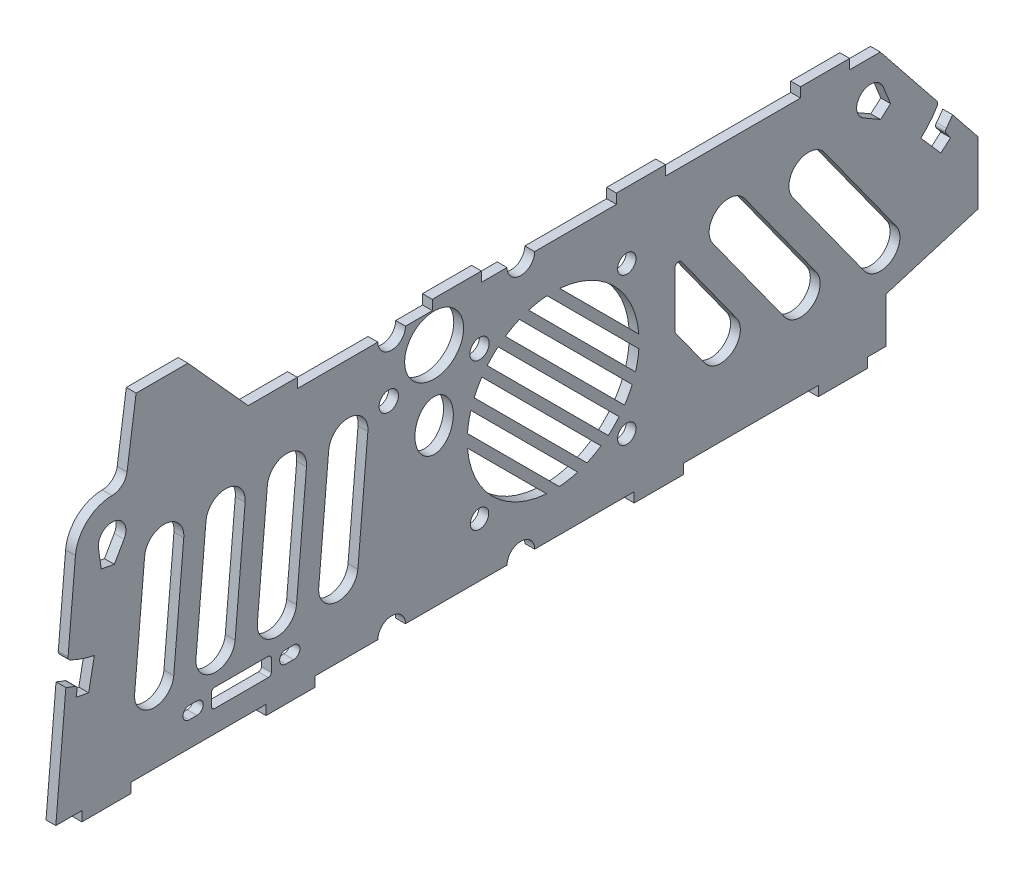
SolidWorks part; units mm, degrees
ref_plane "前视基准面" through (0, 0, 0) normal (0, 0, 1) x (1, 0, 0)
ref_plane "上视基准面" through (0, 0, 0) normal (0, 1, 0) x (1, 0, 0)
ref_plane "右视基准面" through (0, 0, 0) normal (1, 0, 0) x (0, 0, -1)
sketch "右侧结构" plane through (0, 0, 0) normal (1, 0, 0) x (0, 0, -1)
  line L1 (-96.6617, 0) -> (38.5883, 0)
  line L20 (-91.0447, 17.4465) -> (-91.3082, 16.0715)
  line L21 (36.0883, 36) -> (46.5716, 23.9389) construction
  line L22 (37.6933, 42) -> (-87.4892, 42)
  line L23 (-93.4664, 36.5229) -> (-96.6617, 0) construction
  line L25 (38.5883, 0) -> (38.5883, 40.8804) construction
  line L26 (38.5883, 40.8804) -> (37.6933, 42) construction
  line L36 (44.3048, 26.5469) -> (46.5716, 23.9389)
  line L39 (-87.4892, 36) -> (-91.0447, 17.4465) construction
  line L42 (-90.3859, 20.8839) -> (-91.0447, 17.4465)
  line L45 (-93.4664, 36.5229) -> (-94.7017, 22.4034)
  line L48 (-91.3082, 16.0715) -> (-93.3706, 16.4667)
  line L51 (-93.3706, 16.4667) -> (-93.0851, 17.9567)
  line L54 (46.5716, 23.9389) -> (47.5556, 22.8068)
  line L57 (38.5883, 40.8804) -> (53.614, 22.0824) construction
  line L60 (53.614, 22.0824) -> (53.614, 11.8778)
  line L66 (38.5883, 7.3637) -> (38.5883, 0)
  line L69 (47.5556, 22.8068) -> (49.1406, 24.1844)
  line L70 (49.1406, 24.1844) -> (48.1365, 25.5019)
  line L72 (38.1766, 36.8375) -> (39.3635, 33.8782)
  line L73 (39.3635, 33.8782) -> (38.5483, 33.1697)
  line L74 (38.5483, 33.1697) -> (37.7332, 32.4612)
  line L75 (37.7332, 32.4612) -> (34.968, 34.0487)
  line L77 (-88.195, 32.317) -> (-89.2557, 32.5203)
  line L78 (-89.2557, 32.5203) -> (-89.7157, 35.6754)
  line L88 (37.6933, 42) -> (47.164, 30.1517)
  line L91 (-88.195, 32.317) -> (-87.1343, 32.1138)
  line L92 (-87.1343, 32.1138) -> (-85.5405, 34.8753)
  line L97 (42.0237, 24.9708) -> (34.3307, 34.5952) construction
  line L107 (49.4706, 27.266) -> (53.614, 22.0824)
  line L108 (53.614, 11.8778) -> (38.5883, 7.3637)
  line L109 (42.0237, 24.9708) -> (44.209, 22.2369) construction
  line L110 (-95.0276, 18.6781) -> (-96.6617, 0)
  arc A0 (-87.4892, 42) -> (-93.4664, 36.5229) centre (-87.4892, 36) ccw
  circle A21 centre (36.0883, 36) radius 2.25
  arc A23 (47.164, 30.1517) -> (42.0237, 24.9708) centre (36.0883, 36) cw construction
  arc A24 (49.4706, 27.266) -> (44.209, 22.2369) centre (36.0883, 36) cw construction
  arc A25 (47.164, 30.1517) -> (44.3048, 26.5469) centre (36.0883, 36) cw
  arc A28 (49.4706, 27.266) -> (46.5716, 23.9389) centre (36.0883, 36) cw
  circle A31 centre (-87.4892, 36) radius 2.25
  arc A32 (-94.7017, 22.4034) -> (-90.3859, 20.8839) centre (-87.4892, 36) ccw
  arc A33 (-95.0276, 18.6781) -> (-91.0447, 17.4465) centre (-87.4892, 36) ccw
  arc A34 (-44.1822, 42) -> (-39.6822, 42) centre (-41.9322, 42) ccw
  arc A35 (-23.1322, 42) -> (-18.6322, 42) centre (-20.8822, 42) ccw
  arc A37 (-44.1822, 0) -> (-39.6822, 0) centre (-41.9322, 0) cw
  arc A38 (-23.1322, 0) -> (-18.6322, 0) centre (-20.8822, 0) cw
  dimension "D1" = 6
  dimension "D11" = 135.25
  dimension "D13" = 4.5
  dimension "D14" = 6
  dimension "D19" = 3.5
  dimension "D20" = 2.25
  dimension "D30" = 3.75
  dimension "D2" = 42
  dimension "D4" = 7.3637
  dimension "D5" = 15.3911
  dimension "D6" = 21.05
  dimension "D7" = 74.4962
  dimension "D12" = 85
  dimension "D16" = 3.5
  dimension "D17" = 5
  dimension "D18" = 2.5
  dimension "D23" = 1.4
  dimension "D24" = 2.1
  dimension "D25" = 12.3211
  dimension "D26" = 1.5
  dimension "D27" = 2.1
  dimension "D28" = 1.08
  dimension "D29" = 1.08
  dimension "D31" = 1.08
  dimension "D32" = 3.75
  dimension "D33" = 1.08
extrude "凸台-拉伸1" add sketch "右侧结构" along normal blind 1.6
sketch "草图2" plane through (0, 0, 0) normal (1, 0, 0) x (0, 0, -1)
  line L0 (35.5883, 0) -> (35.5883, -1.6)
  line L1 (-83.5777, 54.5) -> (-85.0585, 44.1089)
  line L2 (35.5883, -1.6) -> (27.5883, -1.6)
  line L3 (27.5883, -1.6) -> (27.5883, 0)
  line L4 (27.5883, 0) -> (35.5883, 0)
  line L5 (-83.5777, 54.5) -> (-75.1391, 54.5)
  line L6 (-2.4117, 0) -> (5.5883, 0)
  line L7 (5.5883, 0) -> (5.5883, -1.6)
  line L8 (5.5883, -1.6) -> (-2.4117, -1.6)
  line L9 (-2.4117, -1.6) -> (-2.4117, 0)
  line L10 (-32.4117, 0) -> (-24.4117, 0) construction
  line L11 (-24.4117, 0) -> (-24.4117, -1.6) construction
  line L12 (-24.4117, -1.6) -> (-32.4117, -1.6) construction
  line L13 (-32.4117, -1.6) -> (-32.4117, 0) construction
  line L14 (-62.4117, 0) -> (-54.4117, 0)
  line L15 (-54.4117, 0) -> (-54.4117, -1.6)
  line L16 (-54.4117, -1.6) -> (-62.4117, -1.6)
  line L17 (-62.4117, -1.6) -> (-62.4117, 0)
  line L18 (-92.4117, 0) -> (-84.4117, 0)
  line L19 (-84.4117, 0) -> (-84.4117, -1.6)
  line L20 (-84.4117, -1.6) -> (-92.4117, -1.6)
  line L21 (-92.4117, -1.6) -> (-92.4117, 0)
  line L22 (32.6933, 43.6) -> (32.6933, 42)
  line L23 (32.6933, 42) -> (24.6933, 42)
  line L24 (24.6933, 42) -> (24.6933, 43.6)
  line L25 (24.6933, 43.6) -> (32.6933, 43.6)
  line L26 (-75.1391, 54.5) -> (-65.3067, 43.6)
  line L27 (2.6933, 43.6) -> (2.6933, 42)
  line L28 (2.6933, 42) -> (-5.3067, 42)
  line L29 (-5.3067, 42) -> (-5.3067, 43.6)
  line L30 (-5.3067, 43.6) -> (2.6933, 43.6)
  line L31 (-27.3067, 43.6) -> (-27.3067, 42)
  line L32 (-27.3067, 42) -> (-35.3067, 42)
  line L33 (-35.3067, 42) -> (-35.3067, 43.6)
  line L34 (-35.3067, 43.6) -> (-27.3067, 43.6)
  line L35 (-57.3067, 43.6) -> (-57.3067, 42)
  line L36 (-57.3067, 42) -> (-65.3067, 42)
  line L37 (-65.3067, 42) -> (-65.3067, 43.6) construction
  line L38 (-65.3067, 43.6) -> (-57.3067, 43.6)
  line L39 (38.5883, 7.3637) -> (38.5883, 0) construction
  line L40 (-18.6322, 0) -> (38.5883, 0) construction
  line L41 (37.6933, 42) -> (-18.6322, 42) construction
  line L42 (-87.4892, 42) -> (-65.3067, 42)
  arc A0 (-87.4892, 42) -> (-85.0585, 44.1089) centre (-87.4892, 44.4553) ccw
  dimension "D1" = 3
  dimension "D2" = 1.6
  dimension "D3" = 8
  dimension "D5" = 1.6
  dimension "D6" = 8
  dimension "D7" = 5
  dimension "D9" = 12.5
  dimension "D4" = 5
  dimension "D8" = 4
extrude "上下板接口" add sketch "草图2" along normal up to surface (1.6 mm away) from surface at 0 up to face at (1.6, 34.5298, 87.771) starting at face at (0, 34.5298, 87.771)
sketch "天线接口-草图" plane through (1.6, 0, 0) normal (1, 0, 0) x (0, 0, -1)
  line L0 (38.5883, 0) -> (-117.1754, 0) construction
  line L1 (38.5883, -1000) -> (38.5883, 49000) construction
  line L2 (-42.4117, 32.7972) -> (-27.6117, 32.7972) construction
  line L3 (-35.0117, 25.6459) -> (-35.0117, 32.7972) construction
  line L4 (-35.3067, 42) -> (-39.6822, 42) construction
  circle A7 centre (-42.4117, 32.7972) radius 1.575
  circle A8 centre (-27.6117, 32.7972) radius 1.575
  circle A9 centre (-35.0117, 37) radius 4.8
  ellipse E0 centre (-35.0117, 25.6459) end of major axis (-35.0117, 29.7253) minor radius 3.125
  dimension "D1" = 3.15
  dimension "D2" = 3.125
  dimension "D8" = 5
  dimension "D3" = 3.072
  dimension "D4" = 4.0794
  dimension "D5" = 14.8
  dimension "D6" = 73.6
  dimension "D7" = 32.7972
extrude "天线接口" cut sketch "天线接口-草图" against normal through all
sketch "草图3" plane through (1.6, 0, 0) normal (1, 0, 0) x (0, 0, -1)
  line L0 (-79, 30.5) -> (-80.6317, 11.85) construction
  line L1 (-75.8122, 30.2211) -> (-77.4438, 11.5711)
  line L2 (-82.1878, 30.7789) -> (-83.8195, 12.1289)
  line L3 (-93.4664, 36.5229) -> (-94.7017, 22.4034) construction
  line L6 (26, 30.5) -> (37.685, 14.2685) construction
  line L7 (28.597, 32.3696) -> (40.282, 16.1381)
  line L8 (23.403, 28.6304) -> (35.088, 12.3989)
  line L9 (13, 30.5) -> (24.685, 14.2685) construction
  line L12 (15.597, 32.3696) -> (27.282, 16.1381)
  line L13 (10.403, 28.6304) -> (22.088, 12.3989)
  line L14 (26, 30.5) -> (13, 30.5) construction
  line L15 (26, 30.5) -> (34.8658, 30.5) construction
  line L16 (-69, 30.5) -> (-70.6317, 11.85) construction
  line L17 (-65.8122, 30.2211) -> (-67.4438, 11.5711)
  line L18 (-72.1878, 30.7789) -> (-73.8195, 12.1289)
  line L19 (-79, 30.5) -> (-69, 30.5) construction
  line L20 (4.2233, 24.6335) -> (11.685, 14.2685) construction
  line L23 (5.3102, 28.6008) -> (14.282, 16.1381)
  line L26 (-59, 30.5) -> (-60.6317, 11.85) construction
  line L27 (-55.8122, 30.2211) -> (-57.4438, 11.5711)
  line L28 (-62.1878, 30.7789) -> (-63.8195, 12.1289)
  line L29 (4.3363, 18.9994) -> (9.088, 12.3989)
  line L30 (-49, 30.5) -> (-50.6317, 11.85) construction
  line L31 (-45.8122, 30.2211) -> (-47.4438, 11.5711)
  line L32 (-52.1878, 30.7789) -> (-53.8195, 12.1289)
  line L36 (4.2233, 28.2502) -> (4.2233, 19.3499)
  line L105 (0, 30.5) -> (11.685, 14.2685) construction
  line L106 (2.597, 32.3696) -> (14.282, 16.1381)
  line L107 (-2.597, 28.6304) -> (9.088, 12.3989)
  line L108 (0, 30.5) -> (11.685, 14.2685) construction
  line L109 (2.597, 32.3696) -> (14.282, 16.1381)
  line L110 (-2.597, 28.6304) -> (9.088, 12.3989)
  arc A0 (-75.8122, 30.2211) -> (-82.1878, 30.7789) centre (-79, 30.5) ccw
  arc A1 (-83.8195, 12.1289) -> (-77.4438, 11.5711) centre (-80.6317, 11.85) ccw
  arc A4 (28.597, 32.3696) -> (23.403, 28.6304) centre (26, 30.5) ccw
  arc A5 (35.088, 12.3989) -> (40.282, 16.1381) centre (37.685, 14.2685) ccw
  arc A8 (15.597, 32.3696) -> (10.403, 28.6304) centre (13, 30.5) ccw
  arc A9 (22.088, 12.3989) -> (27.282, 16.1381) centre (24.685, 14.2685) ccw
  arc A10 (-65.8122, 30.2211) -> (-72.1878, 30.7789) centre (-69, 30.5) ccw
  arc A11 (-73.8195, 12.1289) -> (-67.4438, 11.5711) centre (-70.6317, 11.85) ccw
  arc A16 (-55.8122, 30.2211) -> (-62.1878, 30.7789) centre (-59, 30.5) ccw
  arc A17 (-63.8195, 12.1289) -> (-57.4438, 11.5711) centre (-60.6317, 11.85) ccw
  arc A18 (-45.8122, 30.2211) -> (-52.1878, 30.7789) centre (-49, 30.5) ccw
  arc A19 (-53.8195, 12.1289) -> (-47.4438, 11.5711) centre (-50.6317, 11.85) ccw
  arc A21 (9.088, 12.3989) -> (14.282, 16.1381) centre (11.685, 14.2685) ccw
  arc A26 (4.3363, 18.9994) -> (4.2233, 19.3499) centre (4.8233, 19.3499) cw
  arc A27 (4.2233, 28.2502) -> (5.3102, 28.6008) centre (4.8233, 28.2502) cw
  arc A74 (2.597, 32.3696) -> (-2.597, 28.6304) centre (0, 30.5) ccw
  arc A75 (9.088, 12.3989) -> (14.282, 16.1381) centre (11.685, 14.2685) ccw
  point P2 (-79.8158, 21.175)
  point P11 (31.8425, 22.3843)
  point P20 (18.8425, 22.3843)
  point P30 (-69.8158, 21.175)
  point P39 (5.8425, 22.3843)
  point P46 (5.8425, 22.3843)
  point P53 (-59.8158, 21.175)
  point P60 (-49.8158, 21.175)
  point P70 (5.8425, 22.3843)
  point P77 (5.8425, 22.3843)
  point P84 (5.8425, 22.3843)
  point P91 (5.8425, 22.3843)
  point P98 (5.8425, 22.3843)
  point P105 (5.8425, 22.3843)
  point P112 (5.8425, 22.3843)
  point P119 (5.8425, 22.3843)
  point P126 (5.8425, 22.3843)
  point P133 (5.8425, 22.3843)
  point P140 (5.8425, 22.3843)
  point P147 (5.8425, 22.3843)
  point P154 (5.8425, 22.3843)
  point P161 (5.8425, 22.3843)
  point P168 (5.8425, 22.3843)
  point P175 (5.8425, 22.3843)
  point P182 (5.8425, 22.3843)
  point P189 (5.8425, 22.3843)
  point P196 (5.8425, 22.3843)
  point P203 (5.8425, 22.3843)
  point P210 (5.8425, 22.3843)
  point P217 (5.8425, 22.3843)
  point P224 (5.8425, 22.3843)
  point P231 (5.8425, 22.3843)
  dimension "D3" = 3.2
  dimension "D12" = 0.6
  dimension "D2" = 13
  dimension "D4" = 30.5
  dimension "D5" = 26
  dimension "D6" = 54.25
  dimension "D7" = 20
  dimension "D8" = 18.65
  dimension "D9" = 79
  dimension "D11" = 10
  dimension "D1" = 3
  dimension "D10" = 4
extrude "通风口-兼具天线捆扎功能" cut sketch "草图3" against normal through all
sketch "Sketch1" plane through (0, 0, 0) normal (1, 0, 0) x (0, 0, -1)
  line L0 (-70.7867, 6.5881) -> (-62.0367, 6.5881)
  line L1 (-71.2867, 6.0881) -> (-71.2867, 4.0881)
  line L2 (-66.4117, 6.5881) -> (-66.4117, -9.6698) construction
  line L3 (-61.5367, 6.0881) -> (-61.5367, 4.0881)
  line L4 (-71.2867, 5.0881) -> (-66.4117, 5.0881) construction
  line L5 (-70.7867, 3.5881) -> (-62.0367, 3.5881)
  line L8 (-73.6617, 5.0881) -> (-74.9117, 5.0881) construction
  line L9 (-73.6617, 4.0631) -> (-74.9117, 4.0631)
  line L10 (-73.6617, 6.1131) -> (-74.9117, 6.1131)
  line L11 (-59.1617, 5.0881) -> (-57.9117, 5.0881) construction
  line L12 (-59.1617, 4.0631) -> (-57.9117, 4.0631)
  line L13 (-59.1617, 6.1131) -> (-57.9117, 6.1131)
  circle A0 centre (-73.6617, 5.0881) radius 1.025 construction
  circle A1 centre (-59.1617, 5.0881) radius 1.025 construction
  arc A2 (-71.2867, 6.0881) -> (-70.7867, 6.5881) centre (-70.7867, 6.0881) cw
  arc A3 (-71.2867, 4.0881) -> (-70.7867, 3.5881) centre (-70.7867, 4.0881) ccw
  arc A4 (-61.5367, 6.0881) -> (-62.0367, 6.5881) centre (-62.0367, 6.0881) ccw
  arc A5 (-61.5367, 4.0881) -> (-62.0367, 3.5881) centre (-62.0367, 4.0881) cw
  arc A6 (-73.6617, 4.0631) -> (-73.6617, 6.1131) centre (-73.6617, 5.0881) ccw
  arc A7 (-74.9117, 6.1131) -> (-74.9117, 4.0631) centre (-74.9117, 5.0881) ccw
  arc A8 (-59.1617, 4.0631) -> (-59.1617, 6.1131) centre (-59.1617, 5.0881) cw
  arc A9 (-57.9117, 6.1131) -> (-57.9117, 4.0631) centre (-57.9117, 5.0881) cw
  point P17 (-74.2867, 5.0881)
  point P32 (-58.5367, 5.0881)
  dimension "D2" = 2.05
  dimension "D7" = 0.5
  dimension "D1" = 9.75
  dimension "D3" = 3
  dimension "D4" = 14.5
  dimension "D5" = 105
  dimension "D6" = 6.6881
  dimension "D8" = 1.25
extrude "USB-C供电接口" cut sketch "Sketch1" along normal through all
sketch "草图4" plane through (0, 0, 0) normal (-1, 0, 0) x (0, 0, 1)
  line L3 (4.8679, 11.8212) -> (24.5878, 31.5411)
  line L4 (15.6117, 20.7972) -> (27.6117, 8.7972) construction
  line L9 (6.6357, 10.0534) -> (26.3556, 29.7733)
  line L11 (7.8156, 9.1688) -> (27.2401, 28.5934)
  line L12 (10.1071, 7.9248) -> (28.4841, 26.3019)
  line L14 (11.6239, 7.3772) -> (29.0318, 24.785)
  line L15 (14.615, 6.8328) -> (29.5762, 21.794)
  line L17 (16.6852, 6.8385) -> (29.5705, 19.7238)
  line L20 (2.7393, 15.2926) -> (21.1164, 33.6697)
  line L21 (3.9833, 13.0011) -> (23.4079, 32.4256)
  line L23 (1.6472, 19.8005) -> (16.6084, 34.7617)
  line L24 (2.1917, 16.8094) -> (19.5995, 34.2173)
  line L27 (1.6529, 21.8707) -> (14.5383, 34.756)
  circle A2 centre (27.6117, 32.7972) radius 1.5
  circle A6 centre (27.6117, 32.7972) radius 1.575 construction
  circle A7 centre (3.6117, 32.7972) radius 1.5
  circle A8 centre (3.6117, 8.7972) radius 1.5
  circle A9 centre (27.6117, 8.7972) radius 1.5
  arc A23 (2.8913, 26.6446) -> (1.6529, 21.8707) centre (15.6117, 20.7972) ccw
  arc A38 (28.3321, 14.9499) -> (29.5705, 19.7238) centre (15.6117, 20.7972) ccw
  arc A39 (16.6852, 6.8385) -> (21.4591, 8.0769) centre (15.6117, 20.7972) ccw
  arc A40 (11.6239, 7.3772) -> (14.615, 6.8328) centre (15.6117, 20.7972) ccw
  arc A41 (7.8156, 9.1688) -> (10.1071, 7.9248) centre (15.6117, 20.7972) ccw
  arc A42 (4.8679, 11.8212) -> (6.6357, 10.0534) centre (15.6117, 20.7972) ccw
  arc A43 (2.7393, 15.2926) -> (3.9833, 13.0011) centre (15.6117, 20.7972) ccw
  arc A44 (1.6472, 19.8005) -> (2.1917, 16.8094) centre (15.6117, 20.7972) ccw
  arc A45 (14.5383, 34.756) -> (9.7643, 33.5176) centre (15.6117, 20.7972) ccw
  arc A46 (19.5995, 34.2173) -> (16.6084, 34.7617) centre (15.6117, 20.7972) ccw
  arc A47 (23.4079, 32.4256) -> (21.1164, 33.6697) centre (15.6117, 20.7972) ccw
  arc A48 (26.3556, 29.7733) -> (24.5878, 31.5411) centre (15.6117, 20.7972) ccw
  arc A49 (28.4841, 26.3019) -> (27.2401, 28.5934) centre (15.6117, 20.7972) ccw
  arc A50 (29.5762, 21.794) -> (29.0318, 24.785) centre (15.6117, 20.7972) ccw
  arc A51 (9.7643, 33.5176) -> (2.8913, 26.6446) centre (15.6117, 20.7972) ccw
  arc A52 (28.3321, 14.9499) -> (21.4591, 8.0769) centre (15.6117, 20.7972) cw
  point P4 (27.6117, 32.7972)
  point P6 (15.6117, 20.7972)
  point P15 (15.6117, 20.7972)
  point P16 (15.6117, 20.7972)
  point P18 (0, 0)
  point P23 (0, 0)
  point P26 (0, 0)
  point P27 (15.6117, 20.7972)
  point P28 (0, 0)
  point P29 (0, 0)
  point P30 (0, 0)
  point P31 (1.112, 7.9248)
  point P33 (25.1542, 34.9003)
  point P34 (25.6244, 32.4774)
  point P40 (30.2117, 20.7972)
  dimension "D1" = 3
  dimension "D5" = 24
  dimension "D3" = 12
  dimension "D7" = 24
  dimension "D2" = 12
  dimension "D6" = 24
  dimension "D4" = 24
extrude "风扇孔位-借助了天线接口的螺丝孔" cut sketch "草图4" against normal through all
fillet "前后盖板顺滑" radius 0.6 4 edges at (0.8, 25.5019, -48.1365) (0.8, 30.1517, -47.164) (0.8, 17.9567, 93.0851) (0.8, 22.4034, 94.7017)
